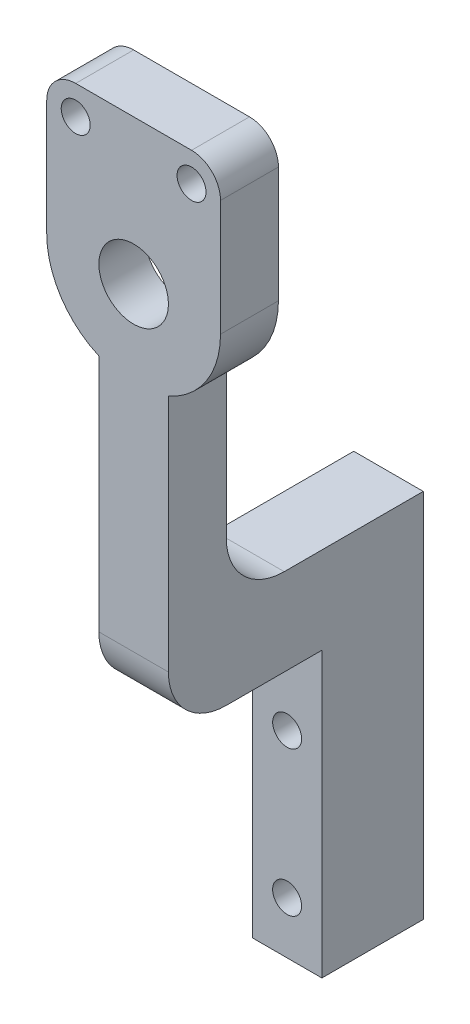
SolidWorks part; units mm, degrees
ref_plane "前视基准面" through (0, 0, 0) normal (0, 0, 1) x (1, 0, 0)
ref_plane "上视基准面" through (0, 0, 0) normal (0, 1, 0) x (1, 0, 0)
ref_plane "右视基准面" through (0, 0, 0) normal (1, 0, 0) x (0, 0, -1)
sketch "草图1" plane through (0, 0, 0) normal (0, 0, 1) x (1, 0, 0)
  circle A0 centre (0, 0) radius 5
  dimension "D1" = 10
extrude "凸台-拉伸1" add sketch "草图1" along normal blind 12.5 contours A0
sketch "草图2" plane through (0, 0, 12.5) normal (0, 0, 1) x (1, 0, 0)
  circle A0 centre (0, 0) radius 6
  dimension "D1" = 12
extrude "凸台-拉伸2" add sketch "草图2" along normal blind 22.5
mirror "镜向2" about plane through (0, 0, 35) normal (0, 0, 1) of "凸台-拉伸2"
sketch "草图3" plane through (0, 0, 57.5) normal (0, 0, 1) x (1, 0, 0)
  circle A0 centre (0, 0) radius 5
  dimension "D1" = 10
extrude "凸台-拉伸3" add sketch "草图3" along normal blind 12.5
sketch "草图4" plane through (0, 0, 0) normal (0, 1, 0) x (1, 0, 0)
  line L0 (-5, -57.5) -> (5, -57.5) construction
  line L1 (6, -12.5) -> (-6, -12.5) construction
  line L2 (6, -57.5) -> (6, -12.5) construction
  line L3 (-6, -12.5) -> (-6, -57.5) construction
  line L4 (-6, -57.5) -> (6, -57.5)
  line L5 (6, -12.5) -> (-6, -12.5)
  line L6 (6, -57.5) -> (6, -12.5)
  line L7 (-6, -12.5) -> (-6, -57.5)
  line L8 (-6, -17.5) -> (6, -17.5)
  line L9 (-6, -52.5) -> (6, -52.5)
  dimension "D1" = 5
  dimension "D2" = 5
extrude "凸台-拉伸4" add sketch "草图4" along normal blind 80 contours L7 L9 L6 L8
sketch "草图5" plane through (-6, 0, 0) normal (-1, 0, 0) x (0, 0, 1)
  line L0 (17.5, 130) -> (52.5, 130) construction
  line L1 (35, 50) -> (35, 100) construction
  line L2 (35, 80) -> (13, 80)
  line L3 (3, 90) -> (3, 130)
  line L4 (17.5, 0) -> (52.5, 0)
  line L5 (52.5, 0) -> (52.5, 80)
  line L6 (52.5, 80) -> (17.5, 80)
  line L7 (17.5, 80) -> (17.5, 0)
  line L8 (17.5, 0) -> (52.5, 0)
  line L9 (52.5, 0) -> (52.5, 80)
  line L10 (52.5, 80) -> (17.5, 80)
  line L11 (17.5, 80) -> (17.5, 0)
  line L12 (3, 130) -> (-7, 130)
  line L13 (-7, 130) -> (-7, 75)
  line L14 (3, 65) -> (17.5, 65)
  line L15 (52.5, 80) -> (59, 80)
  line L16 (69, 90) -> (69, 130)
  line L17 (69, 130) -> (79, 130)
  line L18 (79, 130) -> (79, 75)
  line L19 (69, 65) -> (52.5, 65)
  arc A0 (13, 80) -> (3, 90) centre (13, 90) cw
  arc A1 (3, 65) -> (-7, 75) centre (3, 75) cw
  arc A2 (79, 75) -> (69, 65) centre (69, 75) cw
  arc A3 (69, 90) -> (59, 80) centre (59, 90) cw
  point P16 (3, 80)
  point P28 (69, 80)
  line M10 (17.5, 80) -> (17.5, 0)
  dimension "D6" = 10
  dimension "D7" = 10
  dimension "D11" = 10
  dimension "D2" = 50
  dimension "D3" = 32
  dimension "D4" = 10
  dimension "D5" = 15
  dimension "D8" = 34
  dimension "D9" = 10
  dimension "D10" = 15
  dimension "D1" = 0
extrude "凸台-拉伸5" add sketch "草图5" against normal up to surface (12 mm away) contours A1 L14 L2 A0 L3 L12 L13 M10 | L16 A3 L15 L9 L19 A2 L18 L17 up to face at (6, 40, 35)
sketch "草图6" plane through (0, 0, 69) normal (0, 0, -1) x (-1, 0, 0)
  line L4 (6, 130) -> (-6, 130)
  line L5 (-6, 130) -> (-6, 90)
  line L6 (-6, 90) -> (6, 90)
  line L7 (6, 90) -> (6, 130)
  line L8 (6, 130) -> (-6, 130)
  line L9 (-6, 130) -> (-6, 90)
  line L10 (-6, 90) -> (6, 90)
  line L11 (6, 90) -> (6, 130)
  circle A2 centre (0, 130) radius 15
  line M7 (6, 130) -> (-6, 130)
  line M8 (-6, 130) -> (-6, 90)
  dimension "D3" = 30
  dimension "D1" = 0
extrude "凸台-拉伸6" add sketch "草图6" against normal up to surface (10 mm away) contours L11 A2 M8 M7 up to face at (0, 102.5, 79)
sketch "草图7" plane through (0, 0, 69) normal (0, 0, -1) x (-1, 0, 0)
  arc A0 (6, 116.2523) -> (-6, 116.2523) centre (0, 130) ccw construction
  arc A1 (6, 116.2523) -> (-6, 116.2523) centre (0, 130) ccw
  circle A2 centre (0, 130) radius 9.5
  dimension "D1" = 19
extrude "切除-拉伸1" cut sketch "草图7" against normal blind 2 contours A2
sketch "草图8" plane through (0, 0, 71) normal (0, 0, -1) x (-1, 0, 0)
  circle A0 centre (0, 130) radius 6
  circle A1 centre (0, 130) radius 9.5
  circle A2 centre (0, 130) radius 9.5
  dimension "D2" = 12
  dimension "D1" = 0
extrude "切除-拉伸2" cut sketch "草图8" against normal through all contours A0
sketch "草图9" plane through (0, 0, 79) normal (0, 0, 1) x (1, 0, 0)
  line L0 (-15, 130) -> (-15, 155)
  line L1 (-15, 155) -> (15, 155)
  line L2 (15, 155) -> (15, 130)
  line L3 (-6, 116.2523) -> (-6, 75)
  line L4 (-6, 75) -> (6, 75)
  line L5 (6, 75) -> (6, 116.2523)
  line L6 (-6, 116.2523) -> (-6, 75)
  line L7 (-6, 75) -> (6, 75)
  line L8 (6, 75) -> (6, 116.2523)
  arc A1 (6, 116.2523) -> (-6, 116.2523) centre (0, 130) ccw
  arc A2 (6, 116.2523) -> (-6, 116.2523) centre (0, 130) ccw
  arc M7 (6, 116.2523) -> (-6, 116.2523) centre (0, 130) ccw
  dimension "D2" = 25
  dimension "D1" = 0
extrude "凸台-拉伸7" add sketch "草图9" against normal up to surface (10 mm away) contours L2 L1 L0 M7 up to face at (-9.5, 130, 69)
sketch "草图10" plane through (0, 0, 79) normal (0, 0, 1) x (1, 0, 0)
  line L6 (15, 130) -> (15, 155)
  line L7 (15, 155) -> (-15, 155)
  line L8 (-15, 155) -> (-15, 130)
  line L9 (-6, 116.2523) -> (-6, 75)
  line L10 (-6, 75) -> (6, 75)
  line L11 (6, 75) -> (6, 116.2523)
  line L12 (15, 130) -> (15, 155)
  line L13 (15, 155) -> (-15, 155)
  line L14 (-15, 155) -> (-15, 130)
  line L15 (-6, 116.2523) -> (-6, 75)
  line L16 (-6, 75) -> (6, 75)
  line L17 (6, 75) -> (6, 116.2523)
  circle A0 centre (10, 150) radius 2.5
  arc A2 (6, 116.2523) -> (15, 130) centre (0, 130) ccw
  arc A3 (-15, 130) -> (-6, 116.2523) centre (0, 130) ccw
  arc A4 (6, 116.2523) -> (15, 130) centre (0, 130) ccw
  arc A5 (-15, 130) -> (-6, 116.2523) centre (0, 130) ccw
  dimension "D4" = 5
  dimension "D2" = 5
  dimension "D3" = 5
  dimension "D1" = 0
extrude "切除-拉伸3" cut sketch "草图10" against normal up to surface (10 mm away) contours A0 up to face at (-9.5, 130, 69)
fillet "圆角1" radius 5 1 edges at (15, 155, 74)
fillet "圆角2" radius 5 1 edges at (-15, 155, 74)
sketch "草图11" plane through (0, 0, 79) normal (0, 0, 1) x (1, 0, 0)
  line L6 (10, 155) -> (-10, 155)
  line L7 (-15, 150) -> (-15, 130)
  line L8 (-6, 116.2523) -> (-6, 75)
  line L9 (-6, 75) -> (6, 75)
  line L10 (6, 75) -> (6, 116.2523)
  line L11 (15, 130) -> (15, 150)
  line L12 (10, 155) -> (-10, 155)
  line L13 (-15, 150) -> (-15, 130)
  line L14 (-6, 116.2523) -> (-6, 75)
  line L15 (-6, 75) -> (6, 75)
  line L16 (6, 75) -> (6, 116.2523)
  line L17 (15, 130) -> (15, 150)
  circle A0 centre (-10, 150) radius 2.5
  arc A4 (-10, 155) -> (-15, 150) centre (-10, 150) ccw
  arc A5 (-15, 130) -> (-6, 116.2523) centre (0, 130) ccw
  arc A6 (6, 116.2523) -> (15, 130) centre (0, 130) ccw
  arc A7 (15, 150) -> (10, 155) centre (10, 150) ccw
  arc A8 (-10, 155) -> (-15, 150) centre (-10, 150) ccw
  arc A9 (-15, 130) -> (-6, 116.2523) centre (0, 130) ccw
  arc A10 (6, 116.2523) -> (15, 130) centre (0, 130) ccw
  arc A11 (15, 150) -> (10, 155) centre (10, 150) ccw
  dimension "D2" = 5
  dimension "D1" = 0
extrude "切除-拉伸4" cut sketch "草图11" against normal up to surface (10 mm away) contours A0 up to face at (12.5, 150, 69)
sketch "草图12" plane through (0, 0, 3) normal (0, 0, 1) x (1, 0, 0)
  line L4 (6, 90) -> (6, 130)
  line L5 (6, 130) -> (-6, 130)
  line L6 (-6, 130) -> (-6, 90)
  line L7 (-6, 90) -> (6, 90)
  line L8 (6, 90) -> (6, 130)
  line L9 (6, 130) -> (-6, 130)
  line L10 (-6, 130) -> (-6, 90)
  line L11 (-6, 90) -> (6, 90)
  circle A0 centre (0, 130) radius 27.5
  line M6 (6, 130) -> (-6, 130)
  line M7 (-6, 130) -> (-6, 90)
  dimension "D2" = 55
  dimension "D1" = 0
extrude "凸台-拉伸8" add sketch "草图12" against normal up to surface (10 mm away) contours L8 A0 M7 M6 up to face at (0, 102.5, -7)
sketch "草图13" plane through (0, 0, -7) normal (0, 0, -1) x (-1, 0, 0)
  line L3 (6, 75) -> (6, 103.1625)
  line L4 (-6, 103.1625) -> (-6, 75)
  line L5 (-6, 75) -> (6, 75)
  line L6 (6, 75) -> (6, 103.1625)
  line L7 (-6, 103.1625) -> (-6, 75)
  line L8 (-6, 75) -> (6, 75)
  circle A0 centre (0, 130) radius 20 construction
  arc A1 (6, 103.1625) -> (-6, 103.1625) centre (0, 130) ccw
  arc A2 (6, 103.1625) -> (-6, 103.1625) centre (0, 130) ccw
  circle A3 centre (0, 150) radius 2
  circle A4 centre (0, 130) radius 12.5
  dimension "D2" = 40
  dimension "D3" = 4
  dimension "D4" = 25
  dimension "D1" = 0
extrude "切除-拉伸5" cut sketch "草图13" against normal up to surface (10 mm away) contours A4 | A3 up to face at (0, 110.1656, 3)
pattern_circular "阵列(圆周)1" count 8 over 360 about axis through (0, 130, 0) along (0, 0, 1) of "切除-拉伸5"
sketch "草图14" plane through (0, 0, -7) normal (0, 0, -1) x (-1, 0, 0)
  line L0 (-6, 156.8375) -> (-6, 161.8375)
  line L1 (-1, 166.8375) -> (1, 166.8375)
  line L2 (6, 161.8375) -> (6, 156.8375)
  line L3 (6, 75) -> (6, 103.1625)
  line L4 (-6, 103.1625) -> (-6, 75)
  line L5 (-6, 75) -> (6, 75)
  line L6 (6, 75) -> (6, 103.1625)
  line L7 (-6, 103.1625) -> (-6, 75)
  line L8 (-6, 75) -> (6, 75)
  circle A0 centre (0, 161.8375) radius 2.5
  arc A1 (6, 103.1625) -> (-6, 103.1625) centre (0, 130) ccw
  arc A2 (6, 103.1625) -> (-6, 103.1625) centre (0, 130) ccw
  arc A3 (6, 161.8375) -> (1, 166.8375) centre (1, 161.8375) ccw
  arc A4 (-1, 166.8375) -> (-6, 161.8375) centre (-1, 161.8375) ccw
  point P13 (6, 166.8375)
  point P16 (-6, 166.8375)
  arc M17 (6, 103.1625) -> (-6, 103.1625) centre (0, 130) ccw
  dimension "D4" = 5
  dimension "D6" = 5
  dimension "D2" = 12
  dimension "D3" = 10
  dimension "D5" = 5
  dimension "D1" = 0
extrude "凸台-拉伸9" add sketch "草图14" against normal up to surface (10 mm away) contours L1 A4 L0 L2 A3 A0 M17 up to face at (-12.1421, 115.8579, 3)
sketch "草图15" plane through (0, 0, 17.5) normal (0, 0, -1) x (-1, 0, 0)
  line L3 (6, 65) -> (-6, 65)
  line L4 (-6, 65) -> (-6, 0)
  line L5 (6, 0) -> (6, 65)
  line L6 (6, 65) -> (-6, 65)
  line L7 (-6, 65) -> (-6, 0)
  line L8 (6, 0) -> (6, 65)
  circle A0 centre (0, 25) radius 2.5
  arc A1 (6, 0) -> (-6, 0) centre (0, 0) ccw
  arc A2 (6, 0) -> (-6, 0) centre (0, 0) ccw
  circle A3 centre (0, 50) radius 2.5
  dimension "D4" = 6
  dimension "D5" = 5
  dimension "D6" = 5
  dimension "D2" = 25
  dimension "D3" = 15
  dimension "D1" = 0
extrude "切除-拉伸6" cut sketch "草图15" against normal up to surface (35 mm away) contours A0 | A3 up to face at (0, 34, 52.5)
ref_plane "基准面1" through (0, 0, 35) normal (0, 0, 1) x (1, 0, 0)
sketch "草图16" plane through (0, 0, 35) normal (0, 0, 1) x (1, 0, 0)
  line L0 (-6, 65) -> (-6, 0) construction
  line L1 (6, 65) -> (6, 0) construction
  line L2 (-6, 65) -> (-6, 0)
  line L3 (6, 65) -> (6, 0)
  line L4 (6, 65) -> (6, 97.6533)
  line L5 (6, 97.6533) -> (-6, 97.6533)
  line L6 (-6, 97.6533) -> (-6, 65)
  line L7 (6, 0) -> (-6, 0)
  line L8 (6, 15) -> (-6, 15)
  dimension "D1" = 15
extrude "切除-拉伸7" cut sketch "草图16" against normal through all contours L8 L3 L4 L5 L6 L2
sketch "草图18" plane through (0, 15, 0) normal (0, 1, 0) x (1, 0, 0)
  line L1 (-42.1444, 23.9343) -> (42.1444, 23.9343)
  line L2 (-42.1444, 23.9343) -> (-42.1444, -83.8768)
  line L3 (-42.1444, -83.8768) -> (42.1444, -83.8768)
  line L4 (42.1444, 23.9343) -> (42.1444, -83.8768)
  line L5 (-42.1444, 23.9343) -> (42.1444, -83.8768) construction
  line L6 (-42.1444, -83.8768) -> (42.1444, 23.9343) construction
  point P0 (0, -29.9712)
extrude "切除-拉伸8" cut sketch "草图18" against normal through all and the other way blind 1
